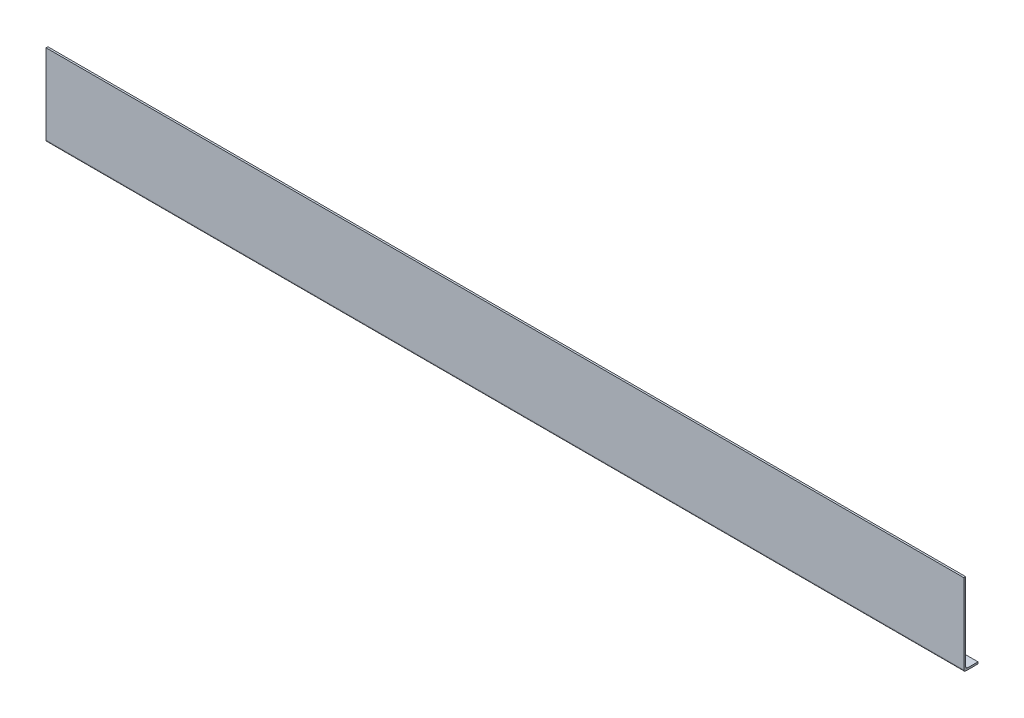
SolidWorks part; units mm, degrees
ref_plane "Front Plane" through (0, 0, 0) normal (0, 0, 1) x (1, 0, 0)
ref_plane "Top Plane" through (0, 0, 0) normal (0, 1, 0) x (1, 0, 0)
ref_plane "Right Plane" through (0, 0, 0) normal (1, 0, 0) x (0, 0, -1)
sketch "Sketch1" plane through (0, 0, 0) normal (1, 0, 0) x (0, 0, -1)
  line L0 (0, 0) -> (-23, 0)
  line L1 (-23, 0) -> (-23, 133)
  line L2 (0, 3) -> (-20, 3)
  line L3 (-20, 3) -> (-20, 133)
  line L4 (-23, 133) -> (-20, 133)
  line L5 (0, 3) -> (0, 0)
  dimension "D1" = 3
  dimension "D2" = 133
  dimension "D3" = 23
extrude "Boss-Extrude1" add sketch "Sketch1" along normal blind 1493
fillet "Fillet1" radius 3 2 edges at (746.5, 3, 20) (746.5, 0, 23)
equation "\"1Bar_Side_RF_3mm_length\"=1493.0"
equation "\"D1@Boss-Extrude1\"= \"1Bar_Side_LF_3mm_length\""
equation "\"CarBeamWidth\"=700.0"
equation "\"WheelWidth\"=650.0"
equation "\"Wheel_FrontBoxDistance\"=1390.0"
equation "\"MetalSheet_3mm_length\"=5030.0"
equation "\"MetalSheet_3mm_width\"=1923.0"
equation "\"MetalSheet_3mm_FloorCut_L_length\"=1764.0"
equation "\"MetalSheet_3mm_FloorCut_L_disdance\"=1665.0"
equation "\"MetalSheet_3mm_FloorCut_R_length\"=1764.0"
equation "\"MetalSheet_3mm_FloorCut_R_disdance\"=1665.0"
equation "\"indoorHeight\"=1940.0"
equation "\"haveDoor_R\"=1"
equation "\"DoorSeparator_RF_3mm_withHinge_toFrontDistance\"=1673.0"
equation "\"DoorSeparator_RF_3mm_withHinge_exist\"=1"
equation "\"DoorSeparator_RB_3mm_withHinge_toFrontDistance\"=3427.0"
equation "\"DoorSeparator_RB_3mm_withHinge_exist\"=1"
equation "\"Door_R1_L_open_Single_toFrontDistance\"=2547.5"
equation "\"Door_R1_L_open_Single_exist\"=1"
equation "\"Door_R1_R_open_Single_toFrontDistance\"=3422.0"
equation "\"Door_R1_R_open_Single_exist\"=1"
equation "\"x\"=66.0"
equation "\"da\"=62.0"
equation "\"SquareTube_length\"=1923.0"
equation "\"channelSteel_length\"=5030.0"
equation "\"SquareTube_inFront_AvgDistance\"=285.0"
equation "\"SquareTube_inFront_TotalCount\"=5"
equation "\"SquareTube_inFront1_cutDepth50_R\"=0.5"
equation "\"SquareTube_inFront1_cutDepth50_L\"=0.5"
equation "\"SquareTube_inFront2_cutDepth50_R\"=0.5"
equation "\"SquareTube_inFront2_cutDepth50_L\"=0.5"
equation "\"SquareTube_inFront3_cutDepth50_R\"=0.5"
equation "\"SquareTube_inFront3_cutDepth50_L\"=0.5"
equation "\"SquareTube_inFront4_cutDepth50_R\"=0.5"
equation "\"SquareTube_inFront4_cutDepth50_L\"=0.5"
equation "\"SquareTube_inFront5_cutDepth50_R\"=50"
equation "\"SquareTube_inFront5_cutDepth50_L\"=50"
equation "\"SquareTube_inFront6_cutDepth50_R\"=50"
equation "\"SquareTube_inFront6_cutDepth50_L\"=50"
equation "\"SquareTube_inFront7_cutDepth50_R\"=50"
equation "\"SquareTube_inFront7_cutDepth50_L\"=50"
equation "\"SquareTube_inFront8_cutDepth50_R\"=50"
equation "\"SquareTube_inFront8_cutDepth50_L\"=50"
equation "\"SquareTube_inFront9_cutDepth50_R\"=50"
equation "\"SquareTube_inFront9_cutDepth50_L\"=50"
equation "\"SquareTube_inFront10_cutDepth50_R\"=50"
equation "\"SquareTube_inFront10_cutDepth50_L\"=50"
equation "\"SquareTube_inFront11_cutDepth50_R\"=50"
equation "\"SquareTube_inFront11_cutDepth50_L\"=50"
equation "\"SquareTube_inFront12_cutDepth50_R\"=50"
equation "\"SquareTube_inFront12_cutDepth50_L\"=50"
equation "\"SquareTube_inFront13_cutDepth50_R\"=50"
equation "\"SquareTube_inFront13_cutDepth50_L\"=50"
equation "\"SquareTube_inFront14_cutDepth50_R\"=50"
equation "\"SquareTube_inFront14_cutDepth50_L\"=50"
equation "\"SquareTube_inBack_AvgDistance\"=333.125"
equation "\"SquareTube_inBack_TotalCount\"=9"
equation "\"SquareTube_inBack1_cutDepth50_R\"=50"
equation "\"SquareTube_inBack1_cutDepth50_L\"=50"
equation "\"SquareTube_inBack2_cutDepth50_R\"=50"
equation "\"SquareTube_inBack2_cutDepth50_L\"=50"
equation "\"SquareTube_inBack3_cutDepth50_R\"=50"
equation "\"SquareTube_inBack3_cutDepth50_L\"=50"
equation "\"SquareTube_inBack4_cutDepth50_R\"=50"
equation "\"SquareTube_inBack4_cutDepth50_L\"=50"
equation "\"SquareTube_inBack5_cutDepth50_R\"=50"
equation "\"SquareTube_inBack5_cutDepth50_L\"=50"
equation "\"SquareTube_inBack6_cutDepth50_R\"=0.5"
equation "\"SquareTube_inBack6_cutDepth50_L\"=0.5"
equation "\"SquareTube_inBack7_cutDepth50_R\"=0.5"
equation "\"SquareTube_inBack7_cutDepth50_L\"=0.5"
equation "\"SquareTube_inBack8_cutDepth50_R\"=0.5"
equation "\"SquareTube_inBack8_cutDepth50_L\"=0.5"
equation "\"boxLength\"=5100.0"
equation "\"boxWidth\"=1930.0"
equation "\"indoorHeight_para\"=25.0"
equation "\"rearLightHeight_para\"=265.0"
equation "\"doorColumnBar_A_FR_3mm_length_Cut\"=2310.0"
equation "\"A\"=0.0"
equation "\"side_door_bottom_R_3mm_length\"=1934.0"
equation "\"side_door_bottom_R_3mm_toFrontDistance\"=1583.0"
equation "\"1Bar_Side_RB_3mm_length\"=1493.0"
equation "\"door_base_long7_R1_L_open_Single_height\"=1890.0"
equation "\"door_base_short7_R1_L_open_Single_height\"=1890.0"
equation "\"door_base_short7_R1_L_open_Single_width\"=864"
equation "\"door_base_long7_R1_R_open_Single_height\"=1890.0"
equation "\"door_base_short7_R1_R_open_Single_height\"=1890.0"
equation "\"door_base_short7_R1_R_open_Single_width\"=864"
equation "\"door_base_double_BL_height\"=1890.0"
equation "\"door_base_short7_BL_Single_height\"=1890.0"
equation "\"door_base_short7_BL_Single_width\"=864"
equation "\"door_base_long7_BR_Single_height\"=1890.0"
equation "\"door_base_short7_BR_Single_height\"=1890.0"
equation "\"door_base_short7_BR_Single_width\"=864"
equation "\"doorColumnBar_A_FL_3mm_length_Cut\"=2310.0"
equation "\"B\"=0.0"
equation "\"haveDoor_L\"=1"
equation "\"side_door_bottom_L_3mm_length\"=1934.0"
equation "\"side_door_bottom_L_3mm_toFrontDistance\"=1583.0"
equation "\"1Bar_Side_LF_3mm_length\"=1493.0"
equation "\"1Bar_Side_LB_3mm_length\"=1493.0"
equation "\"DoorSeparator_LF_3mm_withHinge_toFrontDistance\"=1673.0"
equation "\"DoorSeparator_LF_3mm_withHinge_exist\"=1"
equation "\"DoorSeparator_LB_3mm_withHinge_toFrontDistance\"=3427.0"
equation "\"DoorSeparator_LB_3mm_withHinge_exist\"=1"
equation "\"Door_L1_L_open_Single_toFrontDistance\"=3422.0"
equation "\"Door_L1_L_open_Single_exist\"=1"
equation "\"door_base_long7_L1_L_open_Single_height\"=1890.0"
equation "\"door_base_short7_L1_L_open_Single_height\"=1890.0"
equation "\"door_base_short7_L1_L_open_Single_width\"=864"
equation "\"Door_L1_R_open_Single_toFrontDistance\"=2547.5"
equation "\"Door_L1_R_open_Single_exist\"=1"
equation "\"door_base_long7_L1_R_open_Single_height\"=1890.0"
equation "\"door_base_short7_L1_R_open_Single_height\"=1890.0"
equation "\"door_base_short7_L1_R_open_Single_width\"=864"
